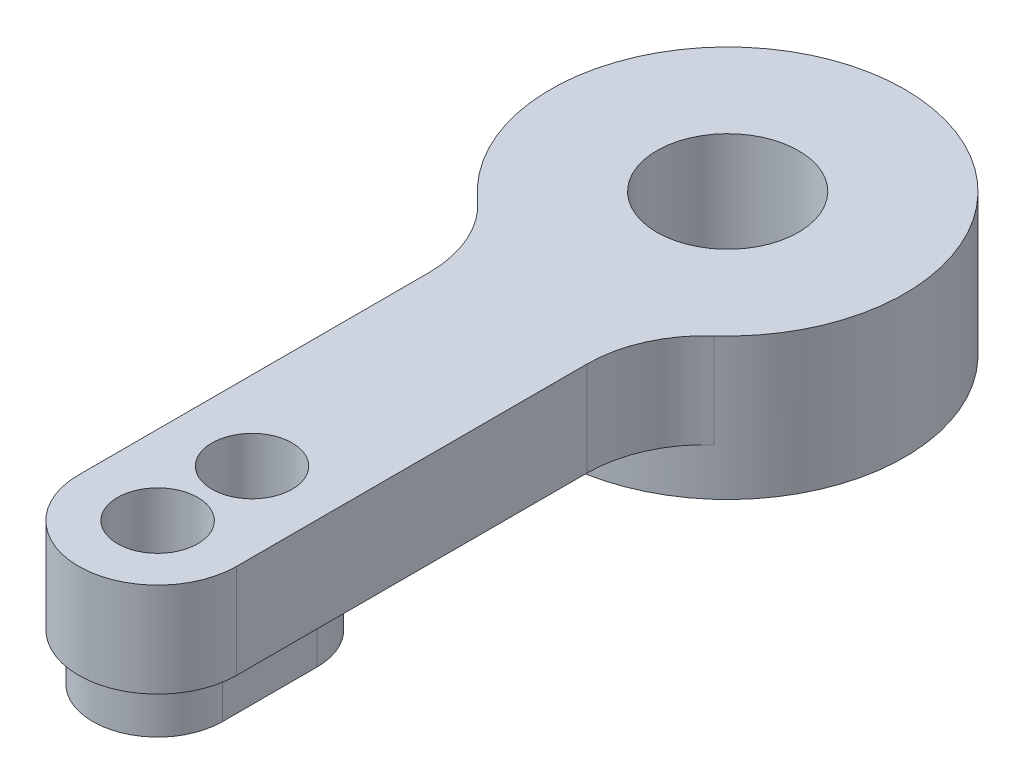
SolidWorks part; units mm, degrees
material "Alliage 1060"
ref_plane "Plan de face" through (0, 0, 0) normal (0, 0, 1) x (1, 0, 0)
ref_plane "Plan de dessus" through (0, 0, 0) normal (0, 1, 0) x (1, 0, 0)
ref_plane "Plan de droite" through (0, 0, 0) normal (1, 0, 0) x (0, 0, -1)
sketch "Esquisse1" plane through (0, 0, 0) normal (0, 1, 0) x (1, 0, 0)
  line L0 (0, 0) -> (0, -24.15) construction
  line L1 (-3.35, -24.15) -> (-3.35, -6.7103)
  line L2 (3.35, -24.15) -> (3.35, -6.7103)
  circle A0 centre (0, 0) radius 3
  arc A1 (3.35, -6.7103) -> (-3.35, -6.7103) centre (0, 0) ccw
  arc A2 (-3.35, -24.15) -> (3.35, -24.15) centre (0, -24.15) ccw
  dimension "D1" = 7.5
  dimension "D2" = 3.35
  dimension "D4" = 6
  dimension "D3" = 24.15
extrude "Boss.-Extru.1" add sketch "Esquisse1" along normal blind 6
sketch "Esquisse2" plane through (0, 0, 0) normal (0, 1, 0) x (1, 0, 0)
  point P0 (0, -24.15)
  point P1 (0, -20.15)
  dimension "D1" = 4
hole_wizard "Dégagement M31" positions "Esquisse4" profile "Esquisse5" hole size "M3" standard "ISO" end condition through all
sketch "Esquisse4" plane through (0, 0, 0) normal (0, -1, 0) x (-1, 0, 0)
  point P0 (0, -24.15)
  point P3 (0, -20.15)
sketch "Esquisse5" plane through (0, 0, 24.15) normal (1, 0, 0) x (0, 0, -1)
  line L0 (0, 0) -> (0, 6)
  line L1 (0, 6) -> (1.7, 6)
  line L2 (1.7, 6) -> (1.7, 0)
  line L5 (1.7, 0) -> (0, 0)
  line L11 (0, -6.35) -> (0, 107.95) construction
  dimension "Diamètre du perçage jusqu'au prochain" = 3.4
  dimension "Profondeur du perçage jusqu'au prochain" = 6
sketch "Esquisse6" plane through (0, 0, 0) normal (0, -1, 0) x (1, 0, 0)
  line L0 (0, 24.15) -> (0, 20.15) construction
  line L1 (2.75, 24.15) -> (2.75, 20.15)
  line L2 (-2.75, 24.15) -> (-2.75, 20.15)
  line L3 (-3.35, 24.15) -> (-3.35, 6.7103)
  line L4 (3.35, 24.15) -> (3.35, 6.7103)
  arc A0 (3.35, 6.7103) -> (-3.35, 6.7103) centre (0, 0) ccw
  arc A2 (2.75, 24.15) -> (-2.75, 24.15) centre (0, 24.15) ccw
  arc A3 (-2.75, 20.15) -> (2.75, 20.15) centre (0, 20.15) ccw
  circle A4 centre (0, 24.15) radius 1.7 construction
  arc A5 (-3.35, 6.7103) -> (3.35, 6.7103) centre (0, 0) ccw construction
  arc A6 (3.35, 24.15) -> (-3.35, 24.15) centre (0, 24.15) ccw
  arc A7 (3.35, 24.15) -> (-3.35, 24.15) centre (0, 24.15) ccw construction
  point P8 (0, 22.15)
  dimension "D2" = 2.75
  dimension "D1" = 4
extrude "Enlèv. mat.-Extru.1" cut sketch "Esquisse6" against normal blind 2
fillet "Congé2" radius 5 2 edges at (-3.35, 4, 6.7103) (3.35, 4, 6.7103)
